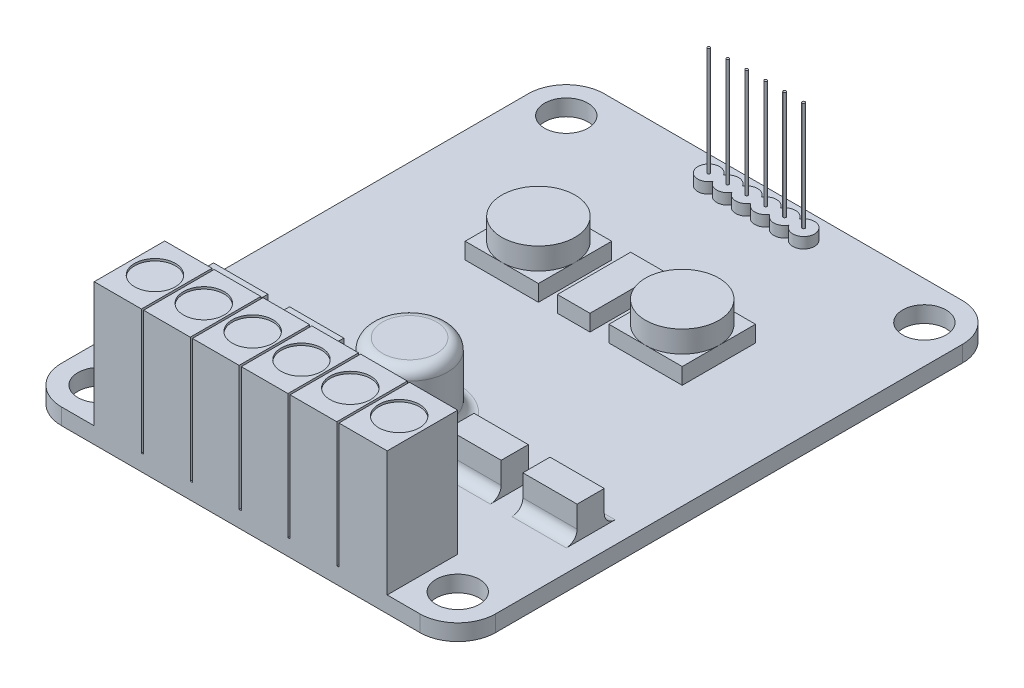
SolidWorks part; units mm, degrees
ref_plane "Front Plane" through (0, 0, 0) normal (0, 0, 1) x (1, 0, 0)
ref_plane "Top Plane" through (0, 0, 0) normal (0, 1, 0) x (1, 0, 0)
ref_plane "Right Plane" through (0, 0, 0) normal (1, 0, 0) x (0, 0, -1)
sketch "Sketch1" plane through (0, 0, 0) normal (0, 1, 0) x (1, 0, 0)
  line L1 (-20, 25) -> (20, 25)
  line L2 (-20, 25) -> (-20, -25)
  line L3 (-20, -25) -> (20, -25)
  line L4 (20, 25) -> (20, -25)
  line L5 (-20, 25) -> (20, -25) construction
  line L6 (-20, -25) -> (20, 25) construction
  point P0 (0, 0)
  dimension "D1" = 50
  dimension "D2" = 40
extrude "Boss-Extrude1" add sketch "Sketch1" along normal blind 1.5
fillet "Fillet1" radius 3.5 4 edges at (20, 0.75, 25) (20, 0.75, -25) (-20, 0.75, -25) (-20, 0.75, 25)
sketch "Sketch2" plane through (0, 1.5, 0) normal (0, 1, 0) x (1, 0, 0)
  circle A0 centre (-16.5, 21.5) radius 2
  circle A1 centre (16.5, 21.5) radius 2
  circle A2 centre (-16.5, -21.5) radius 2
  circle A3 centre (16.5, -21.5) radius 2
  dimension "D1" = 4
extrude "Cut-Extrude1" cut sketch "Sketch2" against normal up to surface (1.5 mm away) up to face at (0, 0, 0)
sketch "Sketch3" plane through (0, 1.5, 0) normal (0, 1, 0) x (1, 0, 0)
  line L0 (-16.5, -25) -> (16.5, -25) construction
  line L1 (-13.5, -25) -> (13.5, -25)
  line L2 (-13.5, -25) -> (-13.5, -18.5)
  line L3 (-13.5, -18.5) -> (13.5, -18.5)
  line L4 (13.5, -25) -> (13.5, -18.5)
  line L5 (-20, 21.5) -> (-20, -21.5) construction
  line L6 (20, -21.5) -> (20, 21.5) construction
  dimension "D1" = 6.5
  dimension "D2" = 6.5
  dimension "D3" = 6.5
extrude "Boss-Extrude2" add sketch "Sketch3" along normal blind 11.5
sketch "Sketch4" plane through (0, 13, 0) normal (0, 1, 0) x (1, 0, 0)
  circle A0 centre (-11.2282, -21.6704) radius 1.875
  circle A1 centre (-6.7282, -21.6704) radius 1.875
  circle A2 centre (-2.2282, -21.6704) radius 1.875
  circle A3 centre (2.2718, -21.6704) radius 1.875
  circle A4 centre (6.7718, -21.6704) radius 1.875
  circle A5 centre (11.2718, -21.6704) radius 1.875
  point P2 (-11.5866, -20.9798)
  point P3 (-11.2558, -20.8017)
  point P14 (-11.3048, -21.0625)
  point P15 (-11.2836, -20.7198)
  point P16 (-11.2282, -21.8293)
  point P17 (-11.2282, -21.6704)
  dimension "D2" = 3.75
  dimension "D1" = 6
extrude "Cut-Extrude2" cut sketch "Sketch4" against normal blind 0.2
sketch "Sketch5" plane through (0, 13, 0) normal (0, 1, 0) x (1, 0, 0)
  line L0 (13.5, -18.5) -> (-13.5, -18.5) construction
  line L1 (-9.1456, -18.5) -> (-8.9456, -18.5)
  line L2 (-9.1456, -18.5) -> (-9.1456, -25)
  line L3 (-9.1456, -25) -> (-8.9456, -25)
  line L4 (-8.9456, -18.5) -> (-8.9456, -25)
  line L5 (-13.5, -25) -> (13.5, -25) construction
  line L6 (-4.6456, -18.5) -> (-4.6456, -25)
  line L7 (-4.4456, -18.5) -> (-4.4456, -25)
  line L8 (-4.6456, -18.5) -> (-4.4456, -18.5)
  line L9 (-4.6456, -25) -> (-4.4456, -25)
  line L10 (-0.1456, -18.5) -> (-0.1456, -25)
  line L11 (0.0544, -18.5) -> (0.0544, -25)
  line L12 (-0.1456, -18.5) -> (0.0544, -18.5)
  line L13 (-0.1456, -25) -> (0.0544, -25)
  line L14 (4.3544, -18.5) -> (4.3544, -25)
  line L15 (4.5544, -18.5) -> (4.5544, -25)
  line L16 (4.3544, -18.5) -> (4.5544, -18.5)
  line L17 (4.3544, -25) -> (4.5544, -25)
  line L18 (8.8544, -18.5) -> (8.8544, -25)
  line L19 (9.0544, -18.5) -> (9.0544, -25)
  line L20 (8.8544, -18.5) -> (9.0544, -18.5)
  line L21 (8.8544, -25) -> (9.0544, -25)
  dimension "D2" = 0.2
  dimension "D1" = 5
extrude "Cut-Extrude3" cut sketch "Sketch5" against normal up to surface (11.5 mm away) up to face at (0, 1.5, 7.25)
sketch "Sketch6" plane through (0, 1.5, 0) normal (0, 1, 0) x (1, 0, 0)
  circle A0 centre (0, -9.4367) radius 3.5
  dimension "D1" = 7
extrude "Boss-Extrude3" add sketch "Sketch6" along normal blind 6
fillet "Fillet2" radius 1 2 edges at (0, 7.5, 12.9367) (0, 1.5, 12.9367)
sketch "Sketch7" plane through (0, 1.5, 0) normal (0, 1, 0) x (1, 0, 0)
  line L0 (20, -21.5) -> (20, 21.5) construction
  line L1 (-6, -9.5) -> (-11, -9.5)
  line L2 (-6, -9.5) -> (-6, -12)
  line L3 (-6, -12) -> (-11, -12)
  line L4 (-11, -9.5) -> (-11, -12)
  line L5 (-13, -9.5) -> (-18, -9.5)
  line L6 (-13, -9.5) -> (-13, -12)
  line L7 (-13, -12) -> (-18, -12)
  line L8 (-18, -9.5) -> (-18, -12)
  line L9 (6, -9.5) -> (11, -9.5)
  line L10 (6, -9.5) -> (6, -12)
  line L11 (6, -12) -> (11, -12)
  line L12 (11, -9.5) -> (11, -12)
  line L13 (13, -9.5) -> (18, -9.5)
  line L14 (13, -9.5) -> (13, -12)
  line L15 (13, -12) -> (18, -12)
  line L16 (18, -9.5) -> (18, -12)
  line L17 (-20, 21.5) -> (-20, -21.5) construction
  line L18 (-16.5, -25) -> (-13.5, -25) construction
  dimension "D1" = 2.5
  dimension "D2" = 5
  dimension "D3" = 2
  dimension "D4" = 9
  dimension "D5" = 2
  dimension "D6" = 9
  dimension "D7" = 13
extrude "Boss-Extrude4" add sketch "Sketch7" along normal blind 3
fillet "Fillet3" radius 1 8 edges at (-8.5, 1.5, 12) (-15.5, 1.5, 12) (-15.5, 1.5, 9.5) (-8.5, 1.5, 9.5) (8.5, 1.5, 9.5) (8.5, 1.5, 12) (15.5, 1.5, 12) (15.5, 1.5, 9.5)
sketch "Sketch8" plane through (0, 1.5, 0) normal (0, 1, 0) x (1, 0, 0)
  line L0 (16.5, 25) -> (-16.5, 25) construction
  arc A0 (-3.5, 22.9841) -> (-3.5, 22.0159) centre (-4.375, 22.5) ccw
  arc A6 (-1.75, 22.9841) -> (-3.5, 22.9841) centre (-2.625, 22.5) ccw
  arc A7 (-1.75, 22.0159) -> (0, 22.0159) centre (-0.875, 22.5) ccw
  arc A8 (0, 22.0159) -> (1.75, 22.0159) centre (0.875, 22.5) ccw
  arc A9 (1.75, 22.0159) -> (3.5, 22.0159) centre (2.625, 22.5) ccw
  arc A10 (3.5, 22.0159) -> (3.5, 22.9841) centre (4.375, 22.5) ccw
  arc A11 (0, 22.9841) -> (-1.75, 22.9841) centre (-0.875, 22.5) ccw
  arc A12 (1.75, 22.9841) -> (0, 22.9841) centre (0.875, 22.5) ccw
  arc A13 (3.5, 22.9841) -> (1.75, 22.9841) centre (2.625, 22.5) ccw
  arc A14 (-3.5, 22.0159) -> (-1.75, 22.0159) centre (-2.625, 22.5) ccw
  point P18 (0, 25)
  dimension "D2" = 2
  dimension "D1" = 2.5
extrude "Boss-Extrude5" add sketch "Sketch8" along normal blind 1
sketch "Sketch9" plane through (0, 2.5, 0) normal (0, 1, 0) x (1, 0, 0)
  circle A0 centre (-4.375, 22.5) radius 0.125
  circle A1 centre (-2.625, 22.5) radius 0.125
  circle A2 centre (-0.875, 22.5) radius 0.125
  circle A3 centre (0.875, 22.5) radius 0.125
  circle A4 centre (2.625, 22.5) radius 0.125
  circle A5 centre (4.375, 22.5) radius 0.125
  dimension "D1" = 0.25
extrude "Boss-Extrude6" add sketch "Sketch9" along normal blind 10
sketch "Sketch10" plane through (0, 1.5, 0) normal (0, 1, 0) x (1, 0, 0)
  line L1 (3.6125, 12.0722) -> (10.3625, 12.0722)
  line L2 (3.6125, 12.0722) -> (3.6125, 5.3222)
  line L3 (3.6125, 5.3222) -> (10.3625, 5.3222)
  line L4 (10.3625, 12.0722) -> (10.3625, 5.3222)
  line L5 (1.8625, 12.0722) -> (-1.1375, 12.0722)
  line L6 (1.8625, 12.0722) -> (1.8625, 5.3222)
  line L7 (1.8625, 5.3222) -> (-1.1375, 5.3222)
  line L8 (-1.1375, 12.0722) -> (-1.1375, 5.3222)
  line L9 (-9.6375, 12.0722) -> (-2.8875, 12.0722)
  line L10 (-9.6375, 12.0722) -> (-9.6375, 5.3222)
  line L11 (-9.6375, 5.3222) -> (-2.8875, 5.3222)
  line L12 (-2.8875, 12.0722) -> (-2.8875, 5.3222)
  dimension "D1" = 6.75
  dimension "D2" = 3
  dimension "D3" = 1.75
  dimension "D4" = 1.75
extrude "Boss-Extrude7" add sketch "Sketch10" along normal blind 1.5
sketch "Sketch11" plane through (0, 3, 0) normal (0, 1, 0) x (1, 0, 0)
  circle A0 centre (-6.2625, 8.6972) radius 3.375
  circle A1 centre (6.9875, 8.6972) radius 3.375
extrude "Boss-Extrude8" add sketch "Sketch11" along normal blind 2
